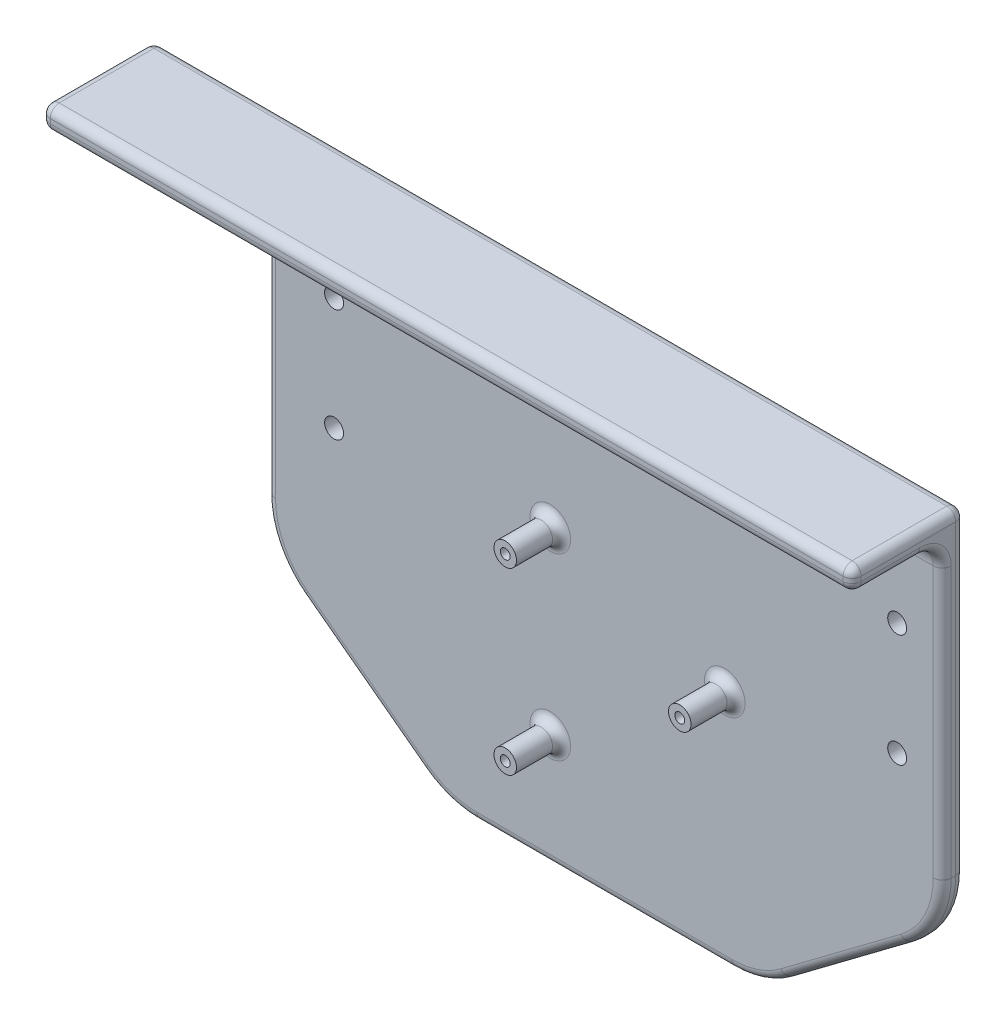
SolidWorks part; units mm, degrees
ref_plane "正面" through (0, 0, 0) normal (0, 0, 1) x (1, 0, 0)
ref_plane "平面" through (0, 0, 0) normal (0, 1, 0) x (1, 0, 0)
ref_plane "右側面" through (0, 0, 0) normal (1, 0, 0) x (0, 0, -1)
sketch "ｽｹｯﾁ1" plane through (0, 0, 0) normal (0, 0, 1) x (1, 0, 0)
  line L0 (-52, -76) -> (-25.3333, -96)
  line L1 (-90, 10) -> (90, 10)
  line L2 (-90, 10) -> (-90, -10)
  line L4 (90, 10) -> (90, -10)
  line L8 (90, -10) -> (90, -60)
  line L10 (-60, -10) -> (-60, -60)
  line L11 (-13.3333, -100) -> (43.3333, -100)
  line L12 (55.3333, -96) -> (82, -76)
  line L15 (-60, -10) -> (-90, -10)
  arc A0 (-60, -60) -> (-52, -76) centre (-40, -60) ccw
  arc A1 (90, -60) -> (82, -76) centre (70, -60) cw
  arc A2 (55.3333, -96) -> (43.3333, -100) centre (43.3333, -80) cw
  arc A3 (-25.3333, -96) -> (-13.3333, -100) centre (-13.3333, -80) ccw
  point P0 (0, 0)
  point P19 (50, -100)
  point P22 (-20, -100)
  dimension "D8" = 20
  dimension "D1" = 180
  dimension "D2" = 20
  dimension "D3" = 50
  dimension "D4" = 30
  dimension "D5" = 50
  dimension "D6" = 40
  dimension "D7" = 40
extrude "ﾎﾞｽ - 押し出し1" add sketch "ｽｹｯﾁ1" along normal blind 5
sketch "ｽｹｯﾁ2" plane through (0, 0, 5) normal (0, 0, 1) x (1, 0, 0)
  line L0 (90, -60) -> (90, 10) construction
  line L1 (90, 10) -> (-90, 10) construction
  circle A0 centre (80, -15) radius 2.1
  circle A1 centre (-45, -15) radius 2.1
  circle A2 centre (80, -40) radius 2.1
  circle A3 centre (-45, -40) radius 2.1
  dimension "D1" = 4.2
  dimension "D2" = 4.2
  dimension "D3" = 4.2
  dimension "D4" = 4.2
  dimension "D5" = 125
  dimension "D7" = 10
  dimension "D8" = 10
  dimension "D9" = 25
  dimension "D10" = 25
  dimension "D11" = 25
  dimension "D12" = 25
  dimension "D6" = 125
extrude "ｶｯﾄ - 押し出し1" cut sketch "ｽｹｯﾁ2" against normal through all
sketch "ｽｹｯﾁ3" plane through (0, 0, 5) normal (0, 0, 1) x (1, 0, 0)
  line L0 (-90, 10) -> (-90, -10) construction
  line L1 (90, 10) -> (-90, 10)
  line L2 (90, 10) -> (90, 5)
  line L3 (90, 5) -> (-90, 5)
  line L4 (-90, 10) -> (-90, 5)
  dimension "D1" = 5
extrude "ﾎﾞｽ - 押し出し3" add sketch "ｽｹｯﾁ3" along normal blind 20
sketch "ｽｹｯﾁ4" plane through (0, 0, 5) normal (0, 0, 1) x (1, 0, 0)
  line L1 (90, -60) -> (90, 5) construction
  line L2 (-13.3333, -100) -> (43.3333, -100) construction
  circle A0 centre (3, -35.2) radius 2.5
  circle A1 centre (41.7413, -47.3437) radius 2.5
  circle A2 centre (3, -75) radius 2.5
  point P6 (0, 0)
  dimension "D1" = 5
  dimension "D2" = 5
  dimension "D3" = 5
  dimension "D4" = 40.6
  dimension "D5" = 47.6
  dimension "D6" = 39.8
  dimension "D7" = 87
  dimension "D8" = 87
  dimension "D9" = 25
extrude "ﾎﾞｽ - 押し出し4" add sketch "ｽｹｯﾁ4" along normal blind 10
fillet "ﾌｨﾚｯﾄ1" radius 5 1 edges at (0, 5, 5)
fillet "ﾌｨﾚｯﾄ2" radius 2 37 edges at (90, -25, 0) (87.8885, -68.9443, 0) (68.6667, -86, 0) (49.6579, -98.9737, 0) (15, -100, 0) (-19.6579, -98.9737, 0) (-38.6667, -86, 0) (-57.8885, -68.9443, 0) (90, 5, 17.5) (90, 3.5355, 6.4645) (90, -30, 5) (87.8885, -68.9443, 5) (68.6667, -86, 5) (49.6579, -98.9737, 5) (15, -100, 5) (-19.6579, -98.9737, 5) (-38.6667, -86, 5) (-57.8885, -68.9443, 5) (-90, 5, 17.5) (-90, 3.5355, 6.4645) (39.2413, -47.3437, 5) (0.5, -35.2, 5) (0.5, -75, 5) (0, 10, 0) (90, 10, 12.5) (0, 10, 25) (0, 5, 25) (-90, 10, 12.5) (-90, 0, 0) (-60, -35, 0) (-75, -10, 0) (-60, -10, 2.5) (-60, -35, 5) (-75, -10, 5) (-90, -5, 5) (-90, 7.5, 25) (90, 7.5, 25)
sketch "ｽｹｯﾁ5" plane through (0, 0, 15) normal (0, 0, 1) x (1, 0, 0)
  circle A0 centre (3, -35.2) radius 1.1
  circle A1 centre (41.7413, -47.3437) radius 1.1
  circle A2 centre (3, -75) radius 1.1
  dimension "D1" = 2.2
  dimension "D2" = 2.2
  dimension "D3" = 2.2
extrude "ｶｯﾄ - 押し出し2" cut sketch "ｽｹｯﾁ5" against normal through all
sketch "ｽｹｯﾁ6" plane through (0, 0, 0) normal (0, 0, -1) x (-1, 0, 0)
  circle A0 centre (-3, -35.2) radius 5
  circle A1 centre (-3, -75) radius 5
  circle A2 centre (-41.7413, -47.3437) radius 5
  dimension "D1" = 10
  dimension "D2" = 10
  dimension "D3" = 10
extrude "ｶｯﾄ - 押し出し3" cut sketch "ｽｹｯﾁ6" against normal blind 2
